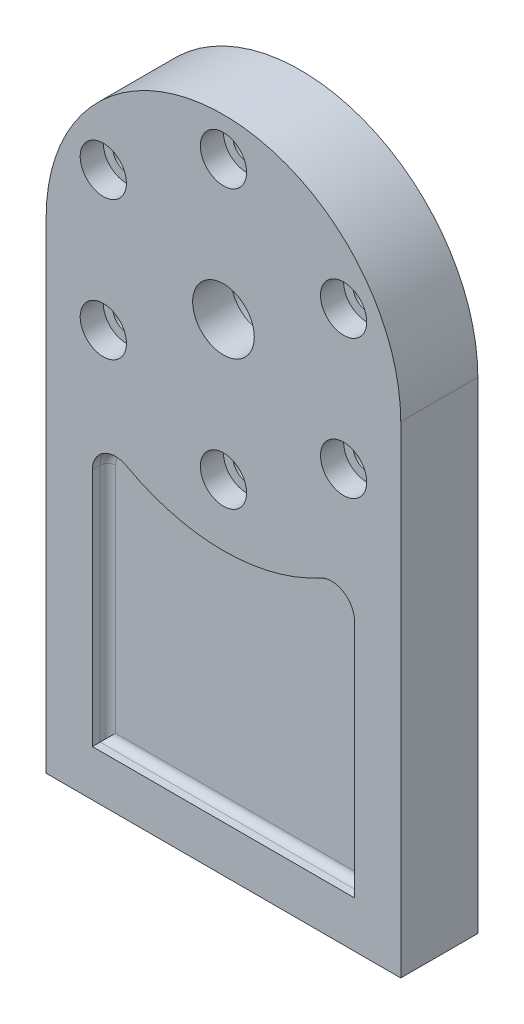
SolidWorks part; units mm, degrees
ref_plane "Front Plane" through (0, 0, 0) normal (0, 0, 1) x (1, 0, 0)
ref_plane "Top Plane" through (0, 0, 0) normal (0, 1, 0) x (1, 0, 0)
ref_plane "Right Plane" through (0, 0, 0) normal (1, 0, 0) x (0, 0, -1)
sketch "Sketch1" plane through (0, 0, 0) normal (0, 0, 1) x (1, 0, 0)
  line L0 (46, 125) -> (46, 0)
  line L1 (46, 0) -> (0, 0)
  line L2 (0, 0) -> (-46, 0)
  line L3 (-46, 0) -> (-46, 125)
  arc A0 (46, 125) -> (-46, 125) centre (0, 125) ccw
  circle A1 centre (0, 125) radius 8
  dimension "D1" = 92
  dimension "D3" = 16
  dimension "D2" = 125
extrude "Boss-Extrude1" add sketch "Sketch1" along normal mid plane 20
sketch "Sketch2" plane through (0, 0, -10) normal (0, 0, -1) x (-1, 0, 0)
  circle A0 centre (0, 125) radius 12.5
  dimension "D1" = 25
extrude "Cut-Extrude1" cut sketch "Sketch2" against normal blind 10
sketch "Sketch4" plane through (0, 0, -10) normal (0, 0, -1) x (-1, 0, 0)
  circle A0 centre (0, 161) radius 3.5
  circle A1 centre (0, 125) radius 36 construction
  point P5 (0, 163.451)
  point P6 (0, 0)
  point P7 (0, 0)
  dimension "D1" = 72
  dimension "D2" = 7
extrude "Cut-Extrude2" cut sketch "Sketch4" against normal through all
sketch "Sketch5" plane through (0, 0, 10) normal (0, 0, 1) x (1, 0, 0)
  circle A0 centre (0, 161) radius 6
  dimension "D1" = 12
extrude "Cut-Extrude3" cut sketch "Sketch5" against normal blind 6
pattern_circular "CirPattern1" count 6 over 360 about axis through (0, 125, 0) along (0, 0, 1) of "Cut-Extrude3", "Cut-Extrude2"
hole_wizard "Tap Drill for M10x1.25 Tap1" positions "Sketch7" profile "Sketch8" hole size "M10x1.25" standard "ISO"
sketch "Sketch7" plane through (0, 0, 0) normal (0, -1, 0) x (-1, 0, 0)
  line L0 (46, -10) -> (-46, -10) construction
  line L1 (-46, -10) -> (-46, 10) construction
  point P0 (-30, 0)
  point P2 (30, 0)
  point P9 (0, 0)
  dimension "D1" = 60
  dimension "D2" = 10
  dimension "D3" = 16
sketch "Sketch8" plane through (30, 0, 0) normal (1, 0, 0) x (0, 0, -1)
  line L0 (0, 0) -> (0, 26.6438)
  line L1 (0, 26.6438) -> (4.4, 24)
  line L2 (4.4, 24) -> (4.4, 0.025)
  line L3 (4.4, 0.025) -> (4.425, 0)
  line L5 (4.425, 0) -> (0, 0)
  line L6 (-4.4, 0.025) -> (-4.425, 0) construction
  line L10 (0, 26.6438) -> (-4.4, 24) construction
  line L11 (0, -6.35) -> (0, 107.95) construction
  dimension "Hole Dia." = 8.8
  dimension "Hole Depth" = 24
  dimension "Near C'Sink Dia." = 8.85
  dimension "Near C'Sink Angle" = 90
  dimension "Drill Angle" = 118
sketch "Sketch9" plane through (0, 0, -10) normal (0, 0, -1) x (-1, 0, 0)
  line L6 (-34, 12) -> (-34, 125)
  line L7 (34, 12) -> (-34, 12)
  line L8 (34, 125) -> (34, 12)
  line L9 (-34, 12) -> (-34, 74.2063)
  line L10 (34, 12) -> (-34, 12)
  line L11 (34, 74.2063) -> (34, 12)
  arc A0 (-25.1034, 79.4608) -> (25.1034, 79.4608) centre (0, 125) ccw
  arc A1 (25.1034, 79.4608) -> (34, 74.2063) centre (28, 74.2063) cw
  arc A2 (-25.1034, 79.4608) -> (-34, 74.2063) centre (-28, 74.2063) ccw
  dimension "D1" = 104
  dimension "D3" = 6
  dimension "D2" = 12
extrude "Cut-Extrude4" cut sketch "Sketch9" against normal blind 4
fillet "Fillet1" radius 2 6 edges at (-34, 43.1031, -6) (0, 12, -6) (34, 43.1031, -6) (31.0513, 79.3725, -6) (0, 73, -6) (-31.0513, 79.3725, -6)
mirror "Mirror1" about plane through (0, 0, 0) normal (0, 0, 1) of "Fillet1", "Cut-Extrude4"
